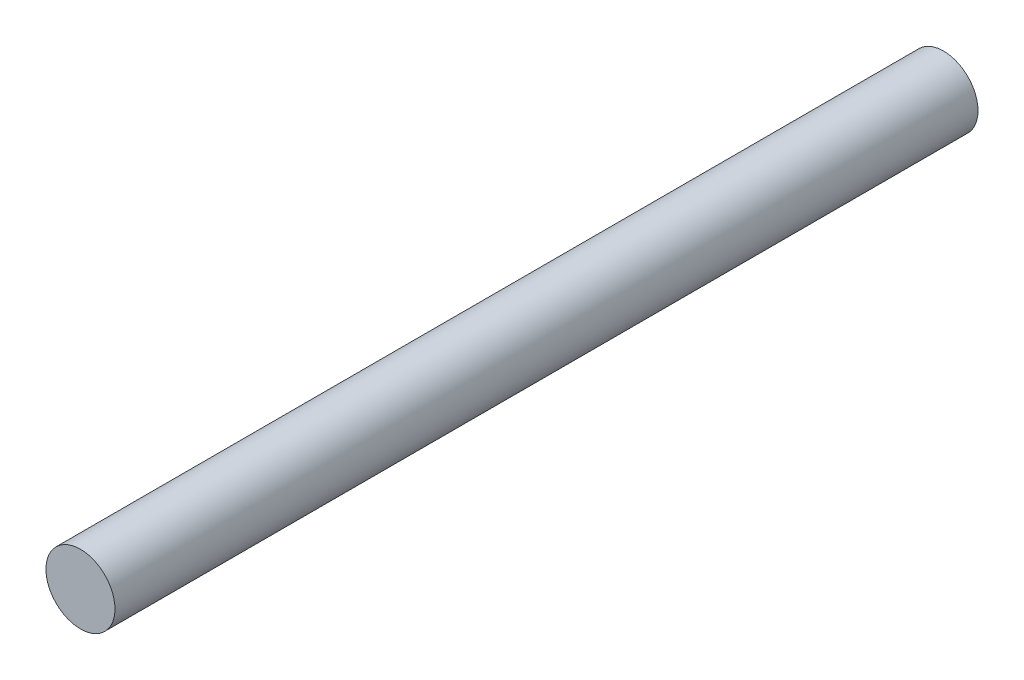
SolidWorks part; units mm, degrees
ref_plane "Front Plane" through (0, 0, 0) normal (0, 0, 1) x (1, 0, 0)
ref_plane "Top Plane" through (0, 0, 0) normal (0, 1, 0) x (1, 0, 0)
ref_plane "Right Plane" through (0, 0, 0) normal (1, 0, 0) x (0, 0, -1)
sketch "Sketch1" plane through (0, 0, 0) normal (0, 0, 1) x (1, 0, 0)
  circle A0 centre (0, 0) radius 20
  dimension "D1" = 40
extrude "Boss-Extrude1" add sketch "Sketch1" along normal blind 500
